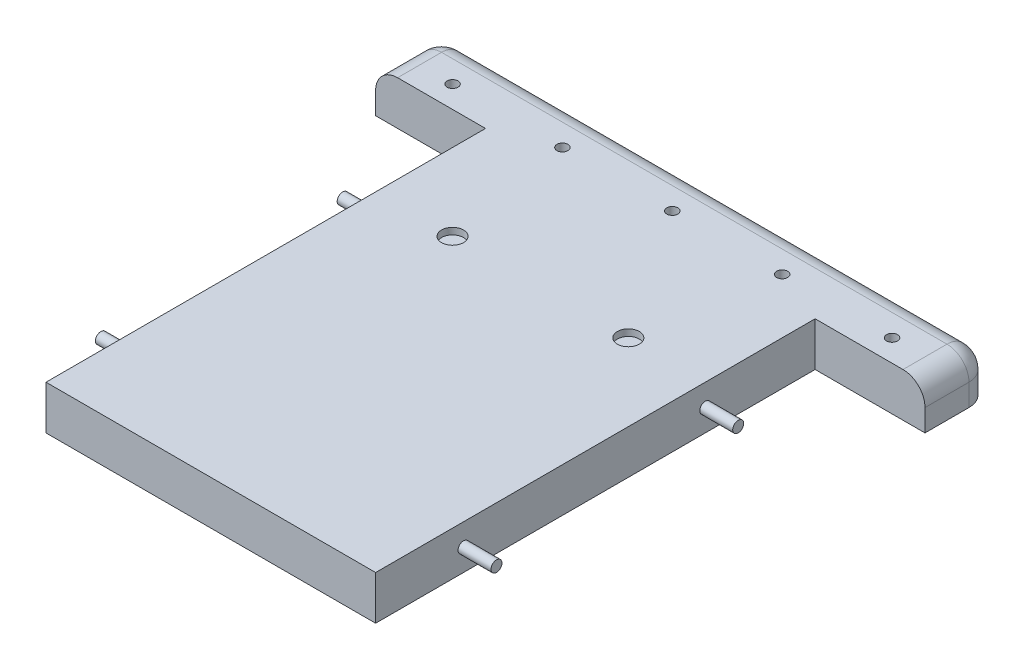
SolidWorks part; units mm, degrees
ref_plane "Front Plane" through (0, 0, 0) normal (0, 0, 1) x (1, 0, 0)
ref_plane "Top Plane" through (0, 0, 0) normal (0, 1, 0) x (1, 0, 0)
ref_plane "Right Plane" through (0, 0, 0) normal (1, 0, 0) x (0, 0, -1)
sketch "Sketch1" plane through (0, 0, 0) normal (0, 1, 0) x (1, 0, 0)
  line L0 (-75, -100) -> (75, -100)
  line L1 (75, -100) -> (75, 100)
  line L2 (75, 100) -> (125, 100)
  line L3 (125, 100) -> (125, 130)
  line L4 (125, 130) -> (-125, 130)
  line L5 (-125, 130) -> (-125, 100)
  line L6 (-125, 100) -> (-75, 100)
  line L7 (-75, 100) -> (-75, -100)
  point P7 (0, -100)
  point P9 (-75, 0)
  dimension "D1" = 250
  dimension "D2" = 30
  dimension "D3" = 150
  dimension "D4" = 200
extrude "Boss-Extrude1" add sketch "Sketch1" along normal blind 20
sketch "Sketch2" plane through (-75, 0, 0) normal (-1, 0, 0) x (0, 0, 1)
  line L0 (100, 20) -> (100, 0) construction
  circle A0 centre (60, 10) radius 2.5
  circle A1 centre (-50, 10) radius 2.5
  point P6 (100, 10)
  dimension "D1" = 5
  dimension "D2" = 40
  dimension "D3" = 110
sketch "Sketch4" plane through (0, 0, 0) normal (0, -1, 0) x (1, 0, 0)
  line L0 (-125, -115) -> (125, -115) construction
  line L1 (-125, -130) -> (-125, -100) construction
  line L2 (125, -100) -> (125, -130) construction
  line L3 (0, -11) -> (0, 11) construction
  circle A0 centre (-100, -115) radius 2.5
  circle A1 centre (-50, -115) radius 2.5
  circle A2 centre (0, -115) radius 2.5
  circle A3 centre (50, -115) radius 2.5
  circle A4 centre (100, -115) radius 2.5
  dimension "D1" = 5
  dimension "D2" = 25
  dimension "D3" = 50
extrude "Cut-Extrude2" cut sketch "Sketch4" against normal blind 5
fillet "Fillet1" radius 10 2 edges at (125, 10, -130) (-125, 10, -130)
fillet "Fillet2" radius 10 5 edges at (125, 20, -110) (122.0711, 20, -127.0711) (-125, 20, -110) (-122.0711, 20, -127.0711) (0, 20, -130)
sketch "Sketch6" plane through (0, 20, 0) normal (0, 1, 0) x (1, 0, 0)
  line L0 (115, 110) -> (-115, 110) construction
  line L1 (115, 100) -> (115, 120) construction
  line L2 (-115, 120) -> (-115, 100) construction
  line L3 (0, -11) -> (0, 11) construction
  circle A0 centre (0, 110) radius 2.5
  circle A1 centre (50, 110) radius 2.5
  circle A2 centre (100, 110) radius 2.5
  circle A3 centre (-50, 110) radius 2.5
  circle A4 centre (-100, 110) radius 2.5
  dimension "D1" = 5
  dimension "D2" = 50
  dimension "D3" = 50
extrude "Cut-Extrude3" cut sketch "Sketch6" against normal blind 5
sketch "Sketch8" plane through (0, 20, 0) normal (0, 1, 0) x (1, 0, 0)
  line L0 (-75, 100) -> (-75, -100) construction
  line L1 (-75, -100) -> (75, -100) construction
  line L2 (0, -11) -> (0, 11) construction
  circle A0 centre (-40, 50) radius 5
  circle A1 centre (40, 50) radius 5
  dimension "D1" = 10
  dimension "D2" = 35
  dimension "D3" = 150
extrude "Cut-Extrude5" cut sketch "Sketch8" against normal blind 3
ref_plane "Plane1" through (0, 10, 0) normal (0, 1, 0) x (1, 0, 0)
extrude "Boss-Extrude2" add sketch "Sketch2" along normal blind 15 and the other way blind 165
